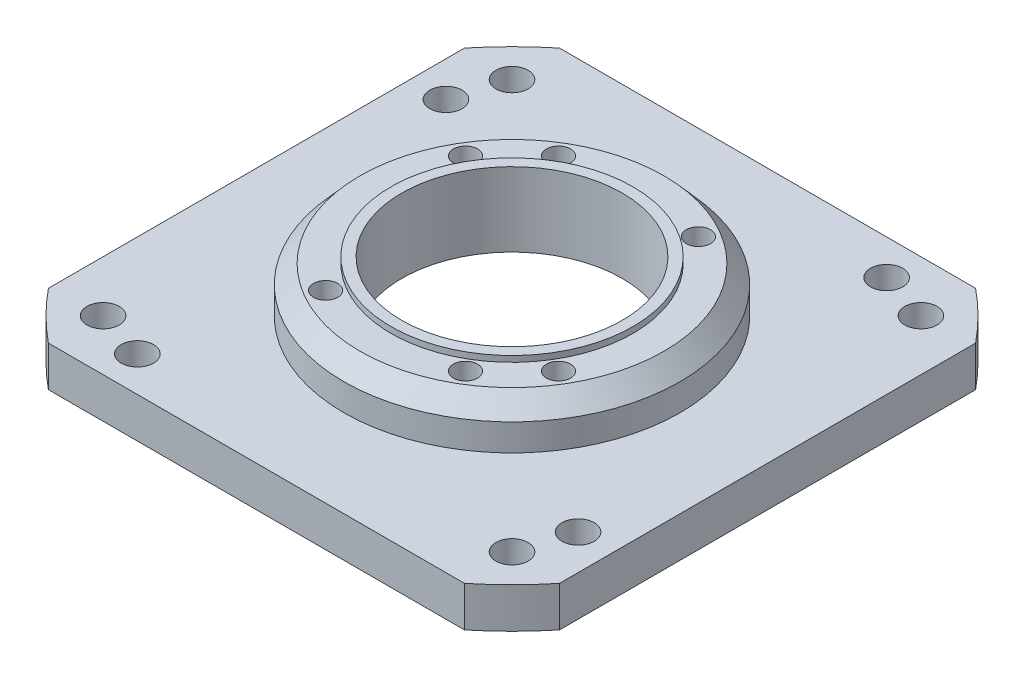
SolidWorks part; units mm, degrees
ref_plane "Front Plane" through (0, 0, 0) normal (0, 0, 1) x (1, 0, 0)
ref_plane "Top Plane" through (0, 0, 0) normal (0, 1, 0) x (1, 0, 0)
ref_plane "Right Plane" through (0, 0, 0) normal (1, 0, 0) x (0, 0, -1)
sketch "Sketch1" plane through (0, 0, 0) normal (0, 1, 0) x (1, 0, 0)
  line L0 (0, 0) -> (0, 95) construction
  line L1 (77.3385, -95) -> (-77.3385, -95)
  line L2 (95, -77.3385) -> (95, 77.3385)
  line L3 (77.3385, 95) -> (-77.3385, 95)
  line L4 (-95, -77.3385) -> (-95, 77.3385)
  line L7 (0, 0) -> (95, 0) construction
  arc A0 (-77.3385, 95) -> (-95, 77.3385) centre (0, 0) ccw
  arc A1 (-95, -77.3385) -> (-77.3385, -95) centre (0, 0) ccw
  arc A2 (77.3385, -95) -> (95, -77.3385) centre (0, 0) ccw
  arc A3 (95, 77.3385) -> (77.3385, 95) centre (0, 0) ccw
  point P0 (0, 0)
  point P15 (-95, 0)
  dimension "D2" = 245
  dimension "D4" = 122.5
  dimension "D3" = 190
extrude "Boss-Extrude1" add sketch "Sketch1" along normal blind 44
sketch "Sketch2" plane through (0, 0, 0) normal (1, 0, 0) x (0, 0, -1)
  line L0 (90, 0) -> (90, 10)
  line L1 (-77.3385, 0) -> (77.3385, 0) construction
  line L2 (90, 10) -> (60, 10)
  line L3 (60, 10) -> (60, 16.5)
  line L4 (60, 16.5) -> (41, 16.5)
  line L5 (41, 16.5) -> (41, 44)
  line L6 (-77.3385, 44) -> (77.3385, 44) construction
  line L7 (41, 44) -> (0, 44)
  line L8 (0, 44) -> (0, 0)
  line L9 (0, 0) -> (90, 0)
  line L10 (0, 0) -> (0, 85.6851) construction
  line L11 (95, 25) -> (62.5, 25) construction
  line L12 (95, 44) -> (95, 0) construction
  line L13 (62.5, 25) -> (62.5, 35) construction
  line L14 (62.5, 35) -> (56.5, 41.8) construction
  line L15 (56.5, 41.8) -> (45, 41.8) construction
  line L16 (45, 41.8) -> (45, 44) construction
  line L17 (45, 44) -> (95, 44) construction
  line L18 (95, 44) -> (95, 25) construction
  dimension "D1" = 180
  dimension "D2" = 120
  dimension "D3" = 82
  dimension "D4" = 10
  dimension "D5" = 6.5
  dimension "D6" = 45
  dimension "D7" = 62.5
  dimension "D8" = 2.2
  dimension "D9" = 113
  dimension "D10" = 25
  dimension "D11" = 10
revolve "Cut-Revolve3" cut sketch "Sketch2" angle 360 about L10
sketch "Sketch3" plane through (0, 0, 0) normal (1, 0, 0) x (0, 0, -1)
  line L1 (95, 25) -> (62.5, 25) construction
  line L2 (62.5, 25) -> (62.5, 35) construction
  line L3 (62.5, 35) -> (56.5, 41.8) construction
  line L4 (56.5, 41.8) -> (45, 41.8) construction
  line L5 (45, 41.8) -> (45, 44) construction
  line L6 (45, 44) -> (95, 44) construction
  line L7 (0, 0) -> (0, 85.6851) construction
  line L9 (132.5, 25) -> (62.5, 25)
  line L10 (62.5, 25) -> (62.5, 35)
  line L11 (62.5, 35) -> (56.5, 41.8)
  line L12 (56.5, 41.8) -> (45, 41.8)
  line L13 (45, 41.8) -> (45, 44)
  line L14 (45, 44) -> (132.5, 44)
  line L15 (0, 0) -> (0, 85.6851) construction
  line L16 (132.5, 25) -> (132.5, 44)
  dimension "D1" = 70
revolve "Cut-Revolve6" cut sketch "Sketch3" angle 360 about L15
sketch "Sketch4" plane through (0, 41.8, 0) normal (0, 1, 0) x (1, 0, 0)
  line L0 (-26, 43.2926) -> (26, 43.2926) construction
  line L1 (26, 43.2926) -> (26, -43.2926) construction
  line L2 (26, -43.2926) -> (-26, -43.2926) construction
  line L3 (-26, -43.2926) -> (-26, 43.2926) construction
  line L4 (-43.2926, 26) -> (43.2926, -26) construction
  line L5 (0, 0) -> (95, 0) construction
  line L6 (95, 77.3385) -> (95, -77.3385) construction
  line L7 (0, 0) -> (0, -95) construction
  line L8 (77.3385, -95) -> (-77.3385, -95) construction
  line L9 (86.6206, -86.6206) -> (0, 0) construction
  circle A0 centre (0, 0) radius 50.5 construction
  circle A1 centre (26, 43.2926) radius 4 construction
  circle A2 centre (-26, 43.2926) radius 4 construction
  circle A3 centre (-26, -43.2926) radius 4 construction
  circle A4 centre (26, -43.2926) radius 4 construction
  circle A5 centre (43.2926, -26) radius 4 construction
  circle A6 centre (-43.2926, 26) radius 4 construction
  arc A7 (77.3385, -95) -> (95, -77.3385) centre (0, 0) ccw construction
  point P18 (0, 0)
  dimension "D1" = 101
  dimension "D3" = 8
  dimension "D2" = 52
hole_wizard "CBORE for M8 Hex Head Bolt1" positions "Sketch5" profile "Sketch7" counterbore size "M8" standard "ANSI Metric" end condition through all
sketch "Sketch5" plane through (0, 16.5, 0) normal (0, -1, 0) x (-1, 0, 0)
  point P0 (-26, 43.2926)
  point P3 (26, 43.2926)
  point P6 (43.2926, 26)
  point P9 (26, -43.2926)
  point P12 (-26, -43.2926)
  point P15 (-43.2926, -26)
sketch "Sketch7" plane through (26, 16.5, -43.2926) normal (1, 0, 0) x (0, 0, -1)
  line L0 (0, 0) -> (0, 27.5)
  line L1 (0, 27.5) -> (4.5, 27.5)
  line L2 (4.5, 13.025) -> (4.5, 27.5)
  line L3 (4.5, 13.025) -> (4.525, 13)
  line L4 (4.525, 13) -> (6.5, 13)
  line L5 (6.5, 13) -> (6.5, 0)
  line L7 (0, 0) -> (6.5, 0)
  line L9 (-4.5, 13.025) -> (-4.525, 13) construction
  line L11 (0, -6.35) -> (0, 107.95) construction
  dimension "Thru Hole Dia." = 9
  dimension "Thru Hole Depth" = 27.5
  dimension "C'Bore Dia." = 13
  dimension "C'Bore Depth" = 13
  dimension "Mid C'Sink Dia." = 9.05
  dimension "Mid C'Sink Angle" = 90
sketch "Sketch8" plane through (0, 10, 0) normal (0, -1, 0) x (1, 0, 0)
  line L0 (57.3576, -81.9152) -> (-81.9152, -57.3576) construction
  line L1 (-76.014, -76.014) -> (76.014, -76.014) construction
  line L2 (-76.014, -76.014) -> (-76.014, 76.014) construction
  line L3 (-76.014, 76.014) -> (76.014, 76.014) construction
  line L4 (76.014, -76.014) -> (76.014, 76.014) construction
  line L5 (-76.014, -76.014) -> (76.014, 76.014) construction
  line L6 (-76.014, 76.014) -> (76.014, -76.014) construction
  line L7 (57.3576, -81.9152) -> (81.9152, 57.3576) construction
  line L8 (-81.9152, -57.3576) -> (-57.3576, 81.9152) construction
  line L9 (81.9152, 57.3576) -> (-57.3576, 81.9152) construction
  line L10 (57.3576, -81.9152) -> (-57.3576, 81.9152) construction
  line L11 (-81.9152, -57.3576) -> (81.9152, 57.3576) construction
  circle A0 centre (76.014, 76.014) radius 6
  circle A1 centre (81.9152, 57.3576) radius 6
  circle A2 centre (76.014, -76.014) radius 6
  circle A3 centre (57.3576, -81.9152) radius 6
  circle A4 centre (-76.014, -76.014) radius 6
  circle A5 centre (-81.9152, -57.3576) radius 6
  circle A6 centre (-76.014, 76.014) radius 6
  circle A7 centre (-57.3576, 81.9152) radius 6
  point P0 (0, 0)
  point P7 (0, 0)
  dimension "D3" = 12
  dimension "D1" = 215
  dimension "D2" = 200
  dimension "D5" = 10
sketch "Sketch9" plane through (0, 10, 0) normal (0, -1, 0) x (1, 0, 0)
  line L1 (-118.4614, -114.1062) -> (118.4614, -114.1062)
  line L2 (-118.4614, -114.1062) -> (-118.4614, 114.1062)
  line L3 (-118.4614, 114.1062) -> (118.4614, 114.1062)
  line L4 (118.4614, -114.1062) -> (118.4614, 114.1062)
  line L5 (-118.4614, -114.1062) -> (118.4614, 114.1062) construction
  line L6 (-118.4614, 114.1062) -> (118.4614, -114.1062) construction
extrude "Cut-Extrude1" cut sketch "Sketch9" along normal blind 10
extrude "Cut-Extrude2" cut sketch "Sketch8" against normal through all
